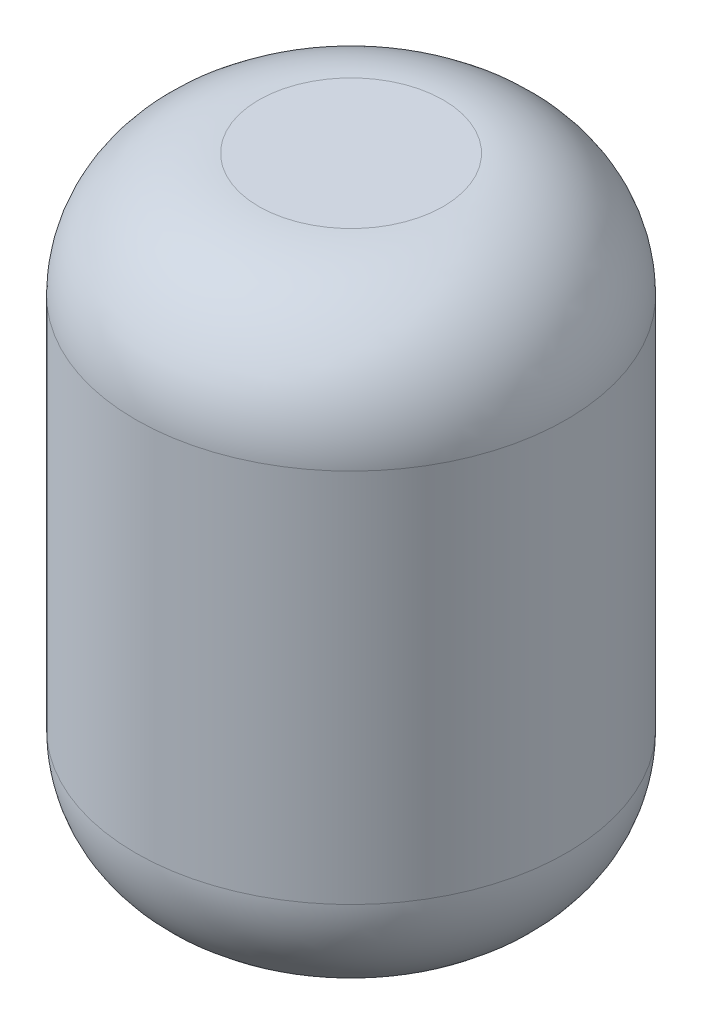
SolidWorks part; units mm, degrees
material "Cast Alloy Steel"
ref_plane "Front Plane" through (0, 0, 0) normal (0, 0, 1) x (1, 0, 0)
ref_plane "Top Plane" through (0, 0, 0) normal (0, 1, 0) x (1, 0, 0)
ref_plane "Right Plane" through (0, 0, 0) normal (1, 0, 0) x (0, 0, -1)
sketch "Sketch1" plane through (0, 0, 0) normal (0, 1, 0) x (1, 0, 0)
  circle A0 centre (0, 0) radius 70
  circle A1 centre (0, 0) radius 68
  dimension "D1" = 140
  dimension "D2" = 2
extrude "Boss-Extrude1" add sketch "Sketch1" along normal blind 200
sketch "Sketch2" plane through (0, 0, 0) normal (0, -1, 0) x (1, 0, 0)
  circle A0 centre (0, 0) radius 70
  dimension "D1" = 140
extrude "Boss-Extrude2" add sketch "Sketch2" against normal blind 2
sketch "Sketch4" plane through (0, 200, 0) normal (0, 1, 0) x (1, 0, 0)
  circle A0 centre (0, 0) radius 70
  dimension "D1" = 140
extrude "Boss-Extrude3" add sketch "Sketch4" along normal blind 2
fillet "Fillet1" radius 40 4 edges at (0, 202, 70) (0, 2, -68) (0, 200, 68) (0, 0, 70)
